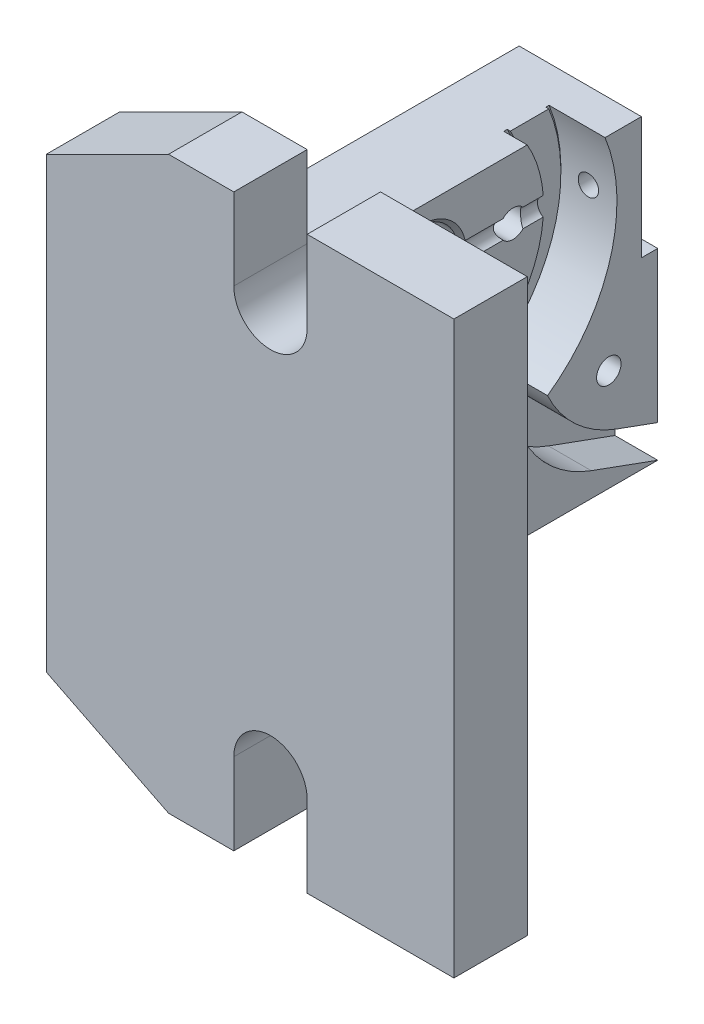
SolidWorks part; units mm, degrees
ref_plane "Спереди" through (0, 0, 0) normal (0, 0, 1) x (1, 0, 0)
ref_plane "Сверху" through (0, 0, 0) normal (0, 1, 0) x (1, 0, 0)
ref_plane "Справа" through (0, 0, 0) normal (1, 0, 0) x (0, 0, -1)
ref_plane "Плоскость4" through (29.9994, 0, 0) normal (1, 0, 0) x (0, 0, -1)
sketch "Эскиз1" plane through (29.9994, 0, 0) normal (1, 0, 0) x (0, 0, -1)
  line L0 (14.9192, 90.0005) -> (0, 90.0005)
  line L1 (0, 90.0005) -> (0, 15.0005)
  line L2 (0, 15.0005) -> (102, 15.0005)
  line L3 (102, 15.0005) -> (85.6938, 20.9355)
  arc A0 (85.6938, 20.9355) -> (67.9664, 38.3248) centre (95.9544, 49.1263) cw
  arc A1 (67.9664, 38.3248) -> (14.9192, 90.0005) centre (52, 75) cw
extrude "Бобышка-Вытянуть1" add sketch "Эскиз1" against normal blind 10.5
sketch "Эскиз2" plane through (19.4994, 0, 0) normal (-1, 0, 0) x (0, 0, 1)
  line L0 (0, 15.0005) -> (-102, 15.0005)
  line L1 (-102, 15.0005) -> (-102, 90.0005)
  line L2 (-102, 90.0005) -> (0, 90.0005)
  line L3 (0, 90.0005) -> (0, 15.0005)
extrude "Бобышка-Вытянуть2" add sketch "Эскиз2" along normal blind 19.4994
sketch "Эскиз3" plane through (0, 0, 0) normal (0, 0, 1) x (1, 0, 0)
  line L0 (29.9994, 0) -> (0, 15.0005)
  line L1 (0, 15.0005) -> (0, 124.9975)
  line L2 (0, 124.9975) -> (29.9976, 140)
  line L3 (29.9976, 140) -> (29.9994, 140)
  line L4 (29.9994, 140) -> (29.9994, 0)
extrude "Бобышка-Вытянуть3" add sketch "Эскиз3" along normal blind 18
sketch "Эскиз4" plane through (29.9994, 0, 0) normal (1, 0, 0) x (0, 0, -1)
  line L0 (-18, 140) -> (0, 140)
  line L1 (0, 140) -> (0, 0)
  line L2 (0, 0) -> (-18, 0)
  line L3 (-18, 0) -> (-18, 140)
extrude "Бобышка-Вытянуть4" add sketch "Эскиз4" along normal blind 70.0006
sketch "Эскиз5" plane through (19.4994, 0, 0) normal (1, 0, 0) x (0, 0, -1)
  line L0 (89.0808, 90.0005) -> (102, 90.0005)
  line L1 (102, 90.0005) -> (102, 23.0005)
  line L2 (102, 23.0005) -> (91.9268, 26.6669)
  arc A0 (91.9268, 26.6669) -> (74.9654, 42.2496) centre (102.1874, 54.8577) cw
  arc A1 (74.9654, 42.2496) -> (89.0808, 90.0005) centre (52, 75) ccw
extrude "Бобышка-Вытянуть5" add sketch "Эскиз5" along normal blind 10.5
ref_plane "Плоскость5" through (16.2494, 0, 0) normal (-1, 0, 0) x (0, -1, 0)
sketch "Эскиз6" plane through (16.2494, 0, 0) normal (-1, 0, 0) x (0, -1, 0)
  line L0 (-90.0005, -14.9192) -> (-90.0005, -89.0808)
  arc A0 (-90.0005, -89.0808) -> (-90.0005, -14.9192) centre (-75, -52) ccw
extrude "Вырез-Вытянуть1" cut sketch "Эскиз6" against normal up to next
sketch "Эскиз7" plane through (0, 0, 0) normal (-1, 0, 0) x (0, 0, 1)
  line L0 (-102, 60.0005) -> (-98, 60.0005)
  line L1 (-98, 60.0005) -> (-98, 90.0005)
  line L2 (-98, 90.0005) -> (-102, 90.0005)
  line L3 (-102, 90.0005) -> (-102, 60.0005)
extrude "Вырез-Вытянуть2" cut sketch "Эскиз7" against normal through all
sketch "Эскиз8" plane through (0, 0, 18) normal (0, 0, 1) x (1, 0, 0)
  line L0 (64, 140) -> (46, 140)
  line L1 (46, 140) -> (46, 120)
  line L2 (64, 120) -> (64, 140)
  arc A0 (46, 120) -> (64, 120) centre (55, 120) ccw
extrude "Вырез-Вытянуть3" cut sketch "Эскиз8" against normal through all
sketch "Эскиз9" plane through (0, 0, 18) normal (0, 0, 1) x (1, 0, 0)
  line L0 (46, 0) -> (64, 0)
  line L1 (64, 0) -> (64, 20)
  line L2 (46, 20) -> (46, 0)
  arc A0 (64, 20) -> (46, 20) centre (55, 20) ccw
extrude "Вырез-Вытянуть4" cut sketch "Эскиз9" against normal through all
sketch "Эскиз10" plane through (16.2494, 0, 0) normal (1, 0, 0) x (0, 0, -1)
  line L0 (15.7295, 90.0005) -> (88.2705, 90.0005)
  arc A0 (88.2705, 90.0005) -> (15.7295, 90.0005) centre (52, 75) cw
extrude "Бобышка-Вытянуть6" add sketch "Эскиз10" along normal blind 0.75
hole_wizard "Отверстие с зазором M521" positions "Эскиз12" profile "Эскиз11" hole size "M52" standard "Ansi Metric"
sketch "Эскиз12" plane through (16.9994, 0, 0) normal (1, 0, 0) x (0, 0, -1)
  point P0 (52, 75)
sketch "Эскиз11" plane through (16.9994, 75, -52) normal (0, 1, 0) x (0, 0, -1)
  line L0 (0, 0) -> (0, 16.9994)
  line L1 (0, 16.9994) -> (30.75, 16.9994)
  line L2 (30.75, 16.9994) -> (30.75, 0)
  line L5 (30.75, 0) -> (0, 0)
  line L11 (0, -6.35) -> (0, 107.95) construction
  dimension "Диаметр сквозного отверстия" = 61.5
  dimension "Глубина сквозного отверстия" = 16.9994
sketch "Эскиз13" plane through (16.2494, 0, 0) normal (-1, 0, 0) x (0, -1, 0)
  line L0 (-90.0005, -26.0196) -> (-90.0005, -77.9804)
  arc A0 (-90.0005, -77.9804) -> (-90.0005, -26.0196) centre (-75, -52) ccw
extrude "Бобышка-Вытянуть7" add sketch "Эскиз13" against normal blind 5.75
hole_wizard "Отверстие1" positions "Эскиз15" profile "Эскиз14" legacy
sketch "Эскиз15" plane through (29.9994, 0, 0) normal (1, 0, 0) x (0, 0, -1)
  point P0 (62, 27.0005)
sketch "Эскиз14" plane through (29.9994, 27.0005, -62) normal (0, 1, 0) x (0, 0, -1)
  line L0 (0, 0) -> (0, 29.9994)
  line L1 (0, 29.9994) -> (3.187, 29.9994)
  line L2 (3.187, 29.9994) -> (3.187, 0)
  line L3 (3.187, 0) -> (0, 0)
  line L4 (0, 110) -> (0, -10) construction
  dimension "Диаметр" = 6.3739
  dimension "Глубина" = 29.9994
hole_wizard "Диаметр отверстия Ø6.7 (6.7)1" positions "Эскиз17" profile "Эскиз16" hole size "Ø6.7" standard "Ansi Metric"
sketch "Эскиз17" plane through (21.9994, 0, 0) normal (1, 0, 0) x (0, 0, -1)
  point P0 (74.5, 75)
  point P1 (29.5, 75)
sketch "Эскиз16" plane through (21.9994, 75, -74.5) normal (0, 1, 0) x (0, 0, -1)
  line L0 (0, 0) -> (0, 5.75)
  line L1 (0, 5.75) -> (3.35, 5.75)
  line L2 (3.35, 5.75) -> (3.35, 0)
  line L5 (3.35, 0) -> (0, 0)
  line L11 (0, -6.35) -> (0, 107.95) construction
  dimension "Диаметр сквозного отверстия" = 6.7
  dimension "Глубина сквозного отверстия" = 5.75
hole_wizard "Диаметр отверстия Ø20.0 (20)1" positions "Эскиз19" profile "Эскиз18" hole size "Ø20.0" standard "Ansi Metric"
sketch "Эскиз19" plane through (21.9994, 0, 0) normal (1, 0, 0) x (0, 0, -1)
  point P0 (52, 75)
sketch "Эскиз18" plane through (21.9994, 75, -52) normal (0, 1, 0) x (0, 0, -1)
  line L0 (0, 0) -> (0, 5.751)
  line L1 (0, 5.751) -> (10, 5.751)
  line L2 (10, 5.751) -> (10, 0)
  line L5 (10, 0) -> (0, 0)
  line L11 (0, -6.35) -> (0, 107.95) construction
  dimension "Диаметр сквозного отверстия" = 20
  dimension "Глубина сквозного отверстия" = 5.751
hole_wizard "Диаметр отверстия Ø4.0 (4)1" positions "Эскиз21" profile "Эскиз20" hole size "Ø4.0" standard "Ansi Metric"
sketch "Эскиз21" plane through (16.9994, 0, 0) normal (1, 0, 0) x (0, 0, -1)
  point P0 (17, 75)
  point P1 (52, 40)
sketch "Эскиз20" plane through (16.9994, 75, -17) normal (0, 1, 0) x (0, 0, -1)
  line L0 (0, 0) -> (0, 16.9994)
  line L1 (0, 16.9994) -> (2, 16.9994)
  line L2 (2, 16.9994) -> (2, 0)
  line L5 (2, 0) -> (0, 0)
  line L11 (0, -6.35) -> (0, 107.95) construction
  dimension "Диаметр сквозного отверстия" = 4
  dimension "Глубина сквозного отверстия" = 16.9994
hole_wizard "Диаметр отверстия Ø6.0 (6)1" positions "Эскиз23" profile "Эскиз22" hole size "Ø6.0" standard "Ansi Metric"
sketch "Эскиз23" plane through (29.9994, 0, 0) normal (1, 0, 0) x (0, 0, -1)
  point P0 (90, 40.0005)
sketch "Эскиз22" plane through (29.9994, 40.0005, -90) normal (0, 1, 0) x (0, 0, -1)
  line L0 (0, 0) -> (0, 30.0004)
  line L1 (0, 30.0004) -> (3, 30.0004)
  line L2 (3, 30.0004) -> (3, 0)
  line L5 (3, 0) -> (0, 0)
  line L11 (0, -6.35) -> (0, 107.95) construction
  dimension "Диаметр сквозного отверстия" = 6
  dimension "Глубина сквозного отверстия" = 30.0004
hole_wizard "Диаметр отверстия Ø5.0 (5)1" positions "Эскиз25" profile "Эскиз24" hole size "Ø5.0" standard "Ansi Metric"
sketch "Эскиз25" plane through (0, 0, -98) normal (0, 0, -1) x (-1, 0, 0)
  point P0 (-23, 75.0005)
sketch "Эскиз24" plane through (23, 75.0005, -98) normal (1, 0, 0) x (0, 1, 0)
  line L0 (0, 0) -> (0, 46)
  line L1 (0, 46) -> (2.5, 46)
  line L2 (2.5, 46) -> (2.5, 0)
  line L5 (2.5, 0) -> (0, 0)
  line L11 (0, -6.35) -> (0, 107.95) construction
  dimension "Диаметр сквозного отверстия" = 5
  dimension "Глубина сквозного отверстия" = 46
hole_wizard "Отверстие с зазором M61" positions "Эскиз27" profile "Эскиз26" hole size "M6" standard "Ansi Metric"
sketch "Эскиз27" plane through (0, 0, -102) normal (0, 0, -1) x (-1, 0, 0)
  point P0 (-15.8867, 33.1286)
sketch "Эскиз26" plane through (15.8867, 33.1286, -102) normal (1, 0, 0) x (0, 1, 0)
  line L0 (0, 0) -> (0, 6)
  line L1 (0, 6) -> (3.2358, 6)
  line L2 (3.2358, 6) -> (3.2358, 0)
  line L5 (3.2358, 0) -> (0, 0)
  line L10 (0, 6) -> (-3.2358, 6) construction
  line L11 (0, -6.35) -> (0, 107.95) construction
  dimension "Диаметр отверстия" = 6.4715
  dimension "Глубина отверстия" = 6
  dimension "Угол заточки сверла" = 180
chamfer "Фаска1" distance 1 angle 45 1 edges at (21.9994, 74.9994, -42)
sketch "Эскиз28" plane through (0, 0, 0) normal (-1, 0, 0) x (0, 0, 1)
  line L0 (-78.843, 90.0005) -> (-25.157, 90.0005)
  circle A0 centre (-29.5, 75) radius 3.35 construction
  circle A1 centre (-52, 75) radius 10 construction
  circle A2 centre (-74.5, 75) radius 3.35 construction
  arc A3 (-78.843, 90.0005) -> (-25.157, 90.0005) centre (-52, 75) ccw construction
  circle A4 centre (-29.5, 75) radius 3.35
  circle A5 centre (-52, 75) radius 10
  circle A6 centre (-74.5, 75) radius 3.35
  arc A7 (-78.843, 90.0005) -> (-25.157, 90.0005) centre (-52, 75) ccw
extrude "Бобышка-Вытянуть8" add sketch "Эскиз28" against normal up to vertex
